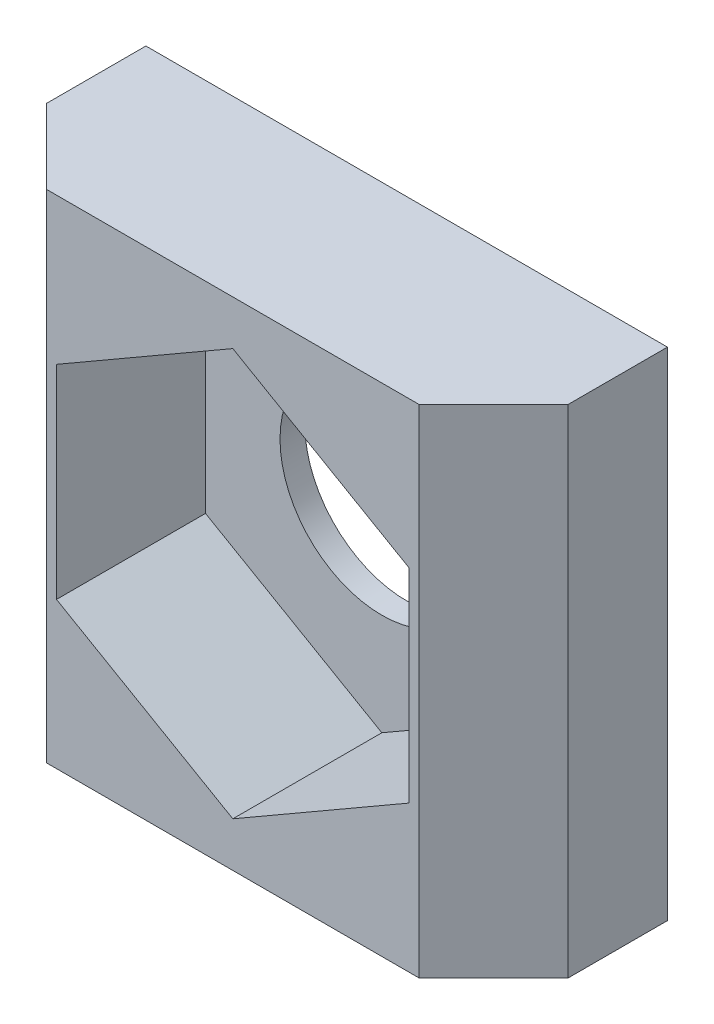
SolidWorks part; units mm, degrees
ref_plane "Plan de face" through (0, 0, 0) normal (0, 0, 1) x (1, 0, 0)
ref_plane "Plan de dessus" through (0, 0, 0) normal (0, 1, 0) x (1, 0, 0)
ref_plane "Plan de droite" through (0, 0, 0) normal (1, 0, 0) x (0, 0, -1)
sketch "Esquisse1" plane through (0, 0, 0) normal (0, 1, 0) x (1, 0, 0)
  line L0 (0, 10.5437) -> (0, -10.1165) construction
  line L1 (-14.3301, 0) -> (20.466, 0) construction
  line L2 (3.75, 0) -> (-3.75, 0)
  line L3 (-3.75, 0) -> (-5.25, 1.5)
  line L4 (-5.25, 1.5) -> (-5.25, 3.5)
  line L5 (-5.25, 3.5) -> (5.25, 3.5)
  line L6 (3.75, 0) -> (5.25, 1.5)
  line L7 (5.25, 1.5) -> (5.25, 3.5)
  point P10 (5.25, 2.5)
  point P11 (0, 0)
  point P13 (0, 3.5)
  dimension "D1" = 10.5
  dimension "D2" = 2
  dimension "D3" = 45
  dimension "3.5" = 3.5
extrude "Boss.-Extru.1" add sketch "Esquisse1" along normal blind 10
sketch "Esquisse4" plane through (0, 0, 0) normal (0, 0, 1) x (1, 0, 0)
  line L0 (0, 0) -> (0, 10) construction
  line L1 (-3.75, 5) -> (3.75, 5) construction
  line L3 (0, 9.0992) -> (-3.55, 7.0496)
  line L4 (-3.75, 0) -> (3.75, 0)
  line L5 (3.75, 0) -> (3.75, 10)
  line L6 (3.75, 10) -> (-3.75, 10)
  line L7 (-3.75, 10) -> (-3.75, 0)
  line L8 (-3.75, 0) -> (3.75, 0)
  line L9 (3.75, 0) -> (3.75, 10)
  line L10 (3.75, 10) -> (-3.75, 10)
  line L11 (-3.75, 10) -> (-3.75, 0)
  line L12 (-3.55, 7.0496) -> (-3.55, 2.9504)
  line L13 (-3.55, 2.9504) -> (0, 0.9008)
  line L14 (0, 0.9008) -> (3.55, 2.9504)
  line L15 (3.55, 2.9504) -> (3.55, 7.0496)
  line L16 (3.55, 7.0496) -> (0, 9.0992)
  circle A0 centre (0, 5) radius 3.55 construction
  line M14 (-3.75, 10) -> (-3.75, 0)
  dimension "D2" = 7.1
  dimension "D1" = 0
extrude "Enlèv. mat.-Extru.2" cut sketch "Esquisse4" against normal blind 3 contours L9 L16 L3 L13 L14 M14 | L12 L13 L3 M14 | L15 L16 L9 L14
sketch "Esquisse5" plane through (0, 0, -3.5) normal (0, 0, -1) x (-1, 0, 0)
  line L0 (-5.25, 5) -> (5.25, 5) construction
  line L1 (0, 0) -> (0, 10) construction
  line L4 (-5.25, 0) -> (5.25, 0)
  line L5 (5.25, 0) -> (5.25, 10)
  line L6 (5.25, 10) -> (-5.25, 10)
  line L7 (-5.25, 10) -> (-5.25, 0)
  line L8 (-5.25, 0) -> (5.25, 0)
  line L9 (5.25, 0) -> (5.25, 10)
  line L10 (5.25, 10) -> (-5.25, 10)
  line L11 (-5.25, 10) -> (-5.25, 0)
  circle A0 centre (0, 5) radius 2.05
  dimension "D2" = 4.1
  dimension "D1" = 0
extrude "Enlèv. mat.-Extru.3" cut sketch "Esquisse5" against normal through all contours A0
